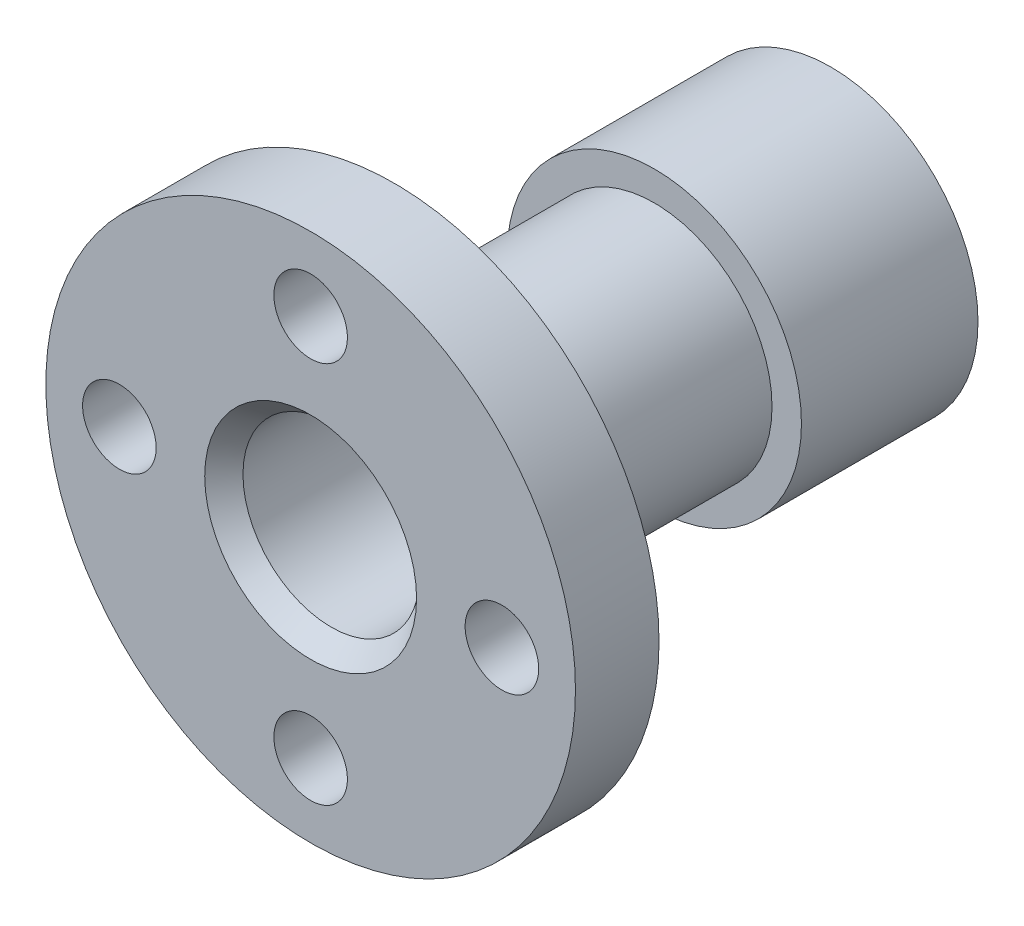
SolidWorks part; units mm, degrees
ref_plane "Alzado" through (0, 0, 0) normal (0, 0, 1) x (1, 0, 0)
ref_plane "Planta" through (0, 0, 0) normal (0, 1, 0) x (1, 0, 0)
ref_plane "Vista lateral" through (0, 0, 0) normal (1, 0, 0) x (0, 0, -1)
sketch "Croquis1" plane through (0, 0, 0) normal (0, 0, 1) x (1, 0, 0)
  circle A0 centre (0, 0) radius 45
  dimension "D1" = 90
extrude "Saliente-Extruir2" add sketch "Croquis1" along normal blind 14.2
sketch "Croquis3" plane through (0, 0, 0) normal (0, 0, 1) x (1, 0, 0)
  circle A0 centre (0, 0) radius 20
  dimension "D1" = 40
extrude "Saliente-Extruir3" add sketch "Croquis3" against normal blind 44.2
sketch "Croquis7" plane through (0, 0, -44.2) normal (0, 0, -1) x (-1, 0, 0)
  circle A0 centre (0, 0) radius 15
  dimension "D1" = 30
extrude "Cortar-Extruir1" cut sketch "Croquis7" against normal up to surface (58.4 mm away) up to face at (45, 0, 14.2)
sketch "Croquis8" plane through (0, 0, -44.2) normal (0, 0, -1) x (-1, 0, 0)
  circle A0 centre (0, 0) radius 25
  dimension "D1" = 50
extrude "Saliente-Extruir7" add sketch "Croquis8" along normal blind 30 contours A0
sketch "Croquis9" plane through (0, 0, -74.2) normal (0, 0, -1) x (-1, 0, 0)
  circle A0 centre (0, 0) radius 19
  dimension "D1" = 38
extrude "Cortar-Extruir2" cut sketch "Croquis9" against normal blind 24 contours A0
sketch "Croquis11" plane through (0, 0, -50.2) normal (0, 0, -1) x (-1, 0, 0)
  circle A0 centre (0, 0) radius 15
  dimension "D1" = 30
extrude "Cortar-Extruir3" cut sketch "Croquis11" against normal blind 6
chamfer "Chaflán1" distance 3.5 distance2 3 1 edges at (15, 0, 14.2)
sketch "Croquis12" plane through (0, 0, 14.2) normal (0, 0, 1) x (1, 0, 0)
  line L0 (0, 0) -> (0, 32.5) construction
  circle A0 centre (0, 32.5) radius 6.25
  circle A1 centre (32.5, 0) radius 6.25
  circle A2 centre (0, -32.5) radius 6.25
  circle A3 centre (-32.5, 0) radius 6.25
  point P13 (0, 0)
  dimension "D1" = 12.5
  dimension "D2" = 32.5
  dimension "D3" = 4
extrude "Cortar-Extruir4" cut sketch "Croquis12" against normal up to surface (14.2 mm away) contours A2 | A3 | A1 | A0 up to face at (20, 0, 0)
